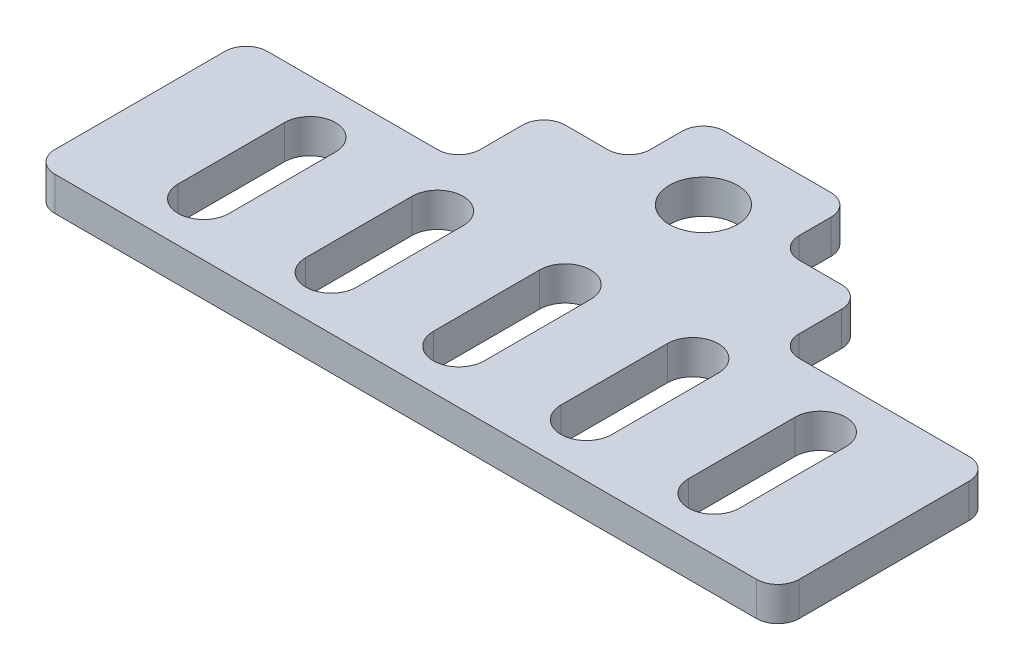
SolidWorks part; units mm, degrees
ref_plane "Front Plane" through (0, 0, 0) normal (0, 0, 1) x (1, 0, 0)
ref_plane "Top Plane" through (0, 0, 0) normal (0, 1, 0) x (1, 0, 0)
ref_plane "Right Plane" through (0, 0, 0) normal (1, 0, 0) x (0, 0, -1)
sketch "Sketch1" plane through (0, 0, 0) normal (0, 1, 0) x (1, 0, 0)
  line L0 (3.5, 2) -> (7.5, 2)
  line L2 (-7.5, -2) -> (-7.5, 2)
  line L3 (-7.5, 2) -> (-3.5, 2)
  line L4 (7.5, -2) -> (7.5, 2)
  line L5 (-7.5, -2) -> (7.5, 2) construction
  line L6 (-7.5, 2) -> (7.5, -2) construction
  line L8 (-3.5, 2) -> (-3.5, 5.5)
  line L9 (-3.5, 5.5) -> (3.5, 5.5)
  line L10 (3.5, 2) -> (3.5, 5.5)
  line L11 (7.5, -2) -> (17.5, -2)
  line L12 (-17.5, -2) -> (-7.5, -2)
  line L13 (-17.5, -2) -> (-17.5, -12)
  line L14 (-17.5, -12) -> (17.5, -12)
  line L15 (17.5, -2) -> (17.5, -12)
  point P0 (0, 0)
  dimension "D1" = 15
  dimension "D2" = 4
  dimension "D3" = 3.5
  dimension "D4" = 4
  dimension "D5" = 4
  dimension "D6" = 10
  dimension "D7" = 10
  dimension "D8" = 10
extrude "Boss-Extrude1" add sketch "Sketch1" along normal blind 1.6
sketch "Sketch2" plane through (0, 1.6, 0) normal (0, 1, 0) x (1, 0, 0)
  line L0 (-3.5, 2) -> (-7.5, 2) construction
  circle A0 centre (0, 2) radius 1.6
  dimension "D1" = 3.2
  dimension "D2" = 0
extrude "Cut-Extrude1" cut sketch "Sketch2" against normal through all
fillet "Fillet1" radius 1 12 edges at (-3.5, 0.8, -2) (-7.5, 0.8, -2) (-7.5, 0.8, 2) (-17.5, 0.8, 2) (-17.5, 0.8, 12) (17.5, 0.8, 12) (17.5, 0.8, 2) (7.5, 0.8, 2) (7.5, 0.8, -2) (3.5, 0.8, -2) (3.5, 0.8, -5.5) (-3.5, 0.8, -5.5)
sketch "Sketch3" plane through (0, 1.6, 0) normal (0, 1, 0) x (1, 0, 0)
  line L0 (0, -9.5) -> (0, -4.5) construction
  line L1 (-1.2, -9.5) -> (-1.2, -4.5)
  line L2 (1.2, -9.5) -> (1.2, -4.5)
  line L3 (16.5, -2) -> (8.5, -2) construction
  arc A0 (-1.2, -9.5) -> (1.2, -9.5) centre (0, -9.5) ccw
  arc A1 (1.2, -4.5) -> (-1.2, -4.5) centre (0, -4.5) ccw
  point P2 (0, -7)
  dimension "D3" = 1.2
  dimension "D1" = 5
  dimension "D2" = 5
extrude "Cut-Extrude2" cut sketch "Sketch3" against normal through all
pattern_linear "LPattern1" count 3 spacing 6 along (1, 0, 0) count 3 spacing 6 along (-1, 0, 0) of "Cut-Extrude2"
